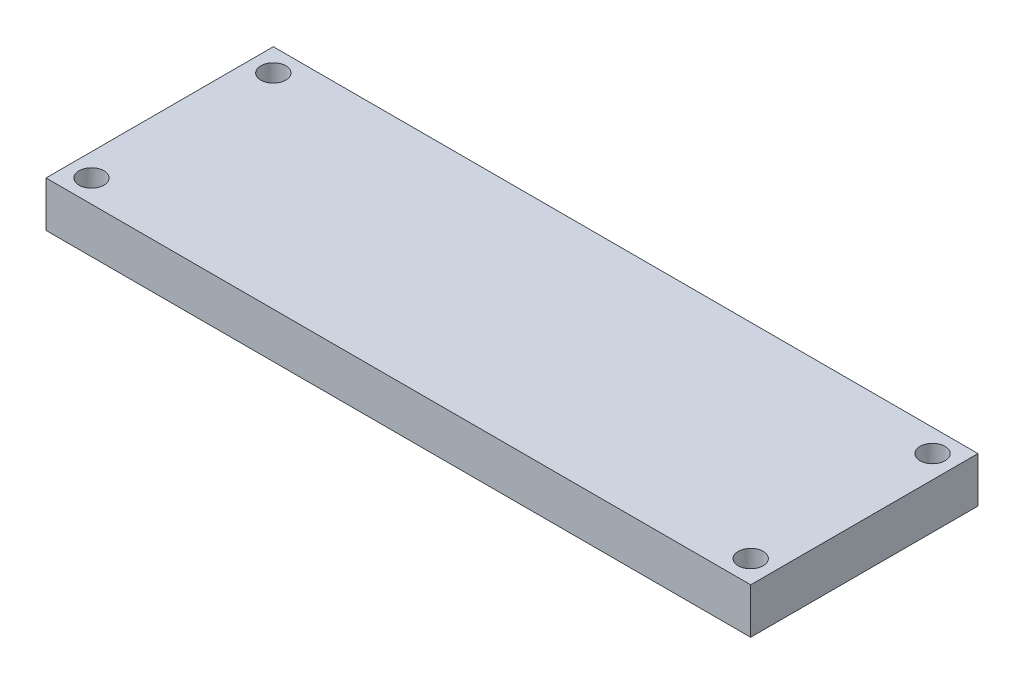
SolidWorks part; units mm, degrees
ref_plane "Front Plane" through (0, 0, 0) normal (0, 0, 1) x (1, 0, 0)
ref_plane "Top Plane" through (0, 0, 0) normal (0, 1, 0) x (1, 0, 0)
ref_plane "Right Plane" through (0, 0, 0) normal (1, 0, 0) x (0, 0, -1)
sketch "Sketch1" plane through (0, 0, 0) normal (0, 1, 0) x (1, 0, 0)
  line L1 (-15.5, -5) -> (15.5, -5)
  line L2 (-15.5, -5) -> (-15.5, 5)
  line L3 (-15.5, 5) -> (15.5, 5)
  line L4 (15.5, -5) -> (15.5, 5)
  line L5 (-15.5, -5) -> (15.5, 5) construction
  line L6 (-15.5, 5) -> (15.5, -5) construction
  circle A0 centre (-14.5, 4) radius 0.55
  circle A1 centre (14.5, 4) radius 0.55
  circle A2 centre (14.5, -4) radius 0.55
  circle A3 centre (-14.5, -4) radius 0.55
  point P0 (0, 0)
  dimension "D3" = 1
  dimension "D1" = 31
  dimension "D2" = 10
  dimension "D4" = 1
  dimension "D7" = 1
  dimension "D5" = 2
  dimension "D6" = 2
extrude "Boss-Extrude1" add sketch "Sketch1" along normal blind 2
